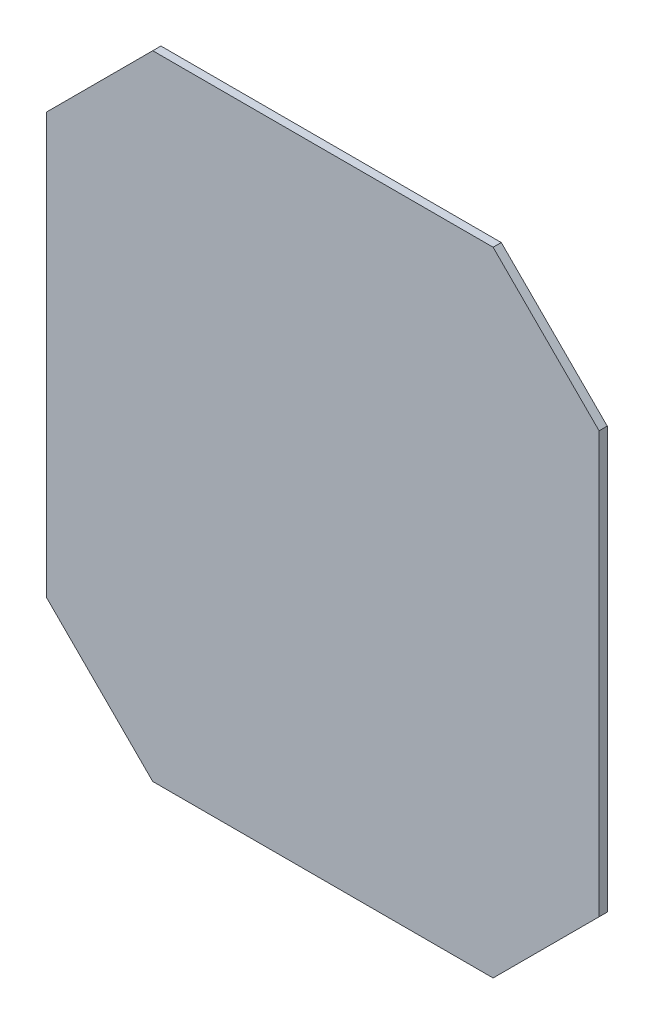
SolidWorks part; units mm, degrees
ref_plane "Front Plane" through (0, 0, 0) normal (0, 0, 1) x (1, 0, 0)
ref_plane "Top Plane" through (0, 0, 0) normal (0, 1, 0) x (1, 0, 0)
ref_plane "Right Plane" through (0, 0, 0) normal (1, 0, 0) x (0, 0, -1)
sketch "Sketch1" plane through (0, 0, 0) normal (0, 0, 1) x (1, 0, 0)
  line L1 (-150.1314, -197.3914) -> (150.1314, -197.3914)
  line L2 (-150.1314, -197.3914) -> (-150.1314, -537.1114)
  line L3 (-150.1314, -537.1114) -> (150.1314, -537.1114)
  line L4 (150.1314, -197.3914) -> (150.1314, -537.1114)
  line L5 (-150.1314, -197.3914) -> (150.1314, -537.1114) construction
  line L6 (-150.1314, -537.1114) -> (150.1314, -197.3914) construction
  line L8 (-150.1314, -477.2514) -> (-129.8686, -477.2514) construction
  line L9 (-129.8686, -477.2514) -> (-89.8686, -517.2514) construction
  line L10 (-89.8686, -517.2514) -> (-89.8686, -537.1114) construction
  line L14 (-129.4544, -476.2514) -> (-88.8686, -516.8372)
  line L15 (-88.8686, -516.8372) -> (-88.8686, -537.1114)
  line L16 (-129.4544, -476.2514) -> (-150.1314, -476.2514)
  line L17 (0, -113.8731) -> (0, -620.6296) construction
  line L18 (88.8686, -516.8372) -> (88.8686, -537.1114)
  line L19 (89.8686, -517.2514) -> (89.8686, -537.1114) construction
  line L20 (129.8686, -477.2514) -> (89.8686, -517.2514) construction
  line L21 (129.4544, -476.2514) -> (88.8686, -516.8372)
  line L22 (129.4544, -476.2514) -> (150.1314, -476.2514)
  line L23 (150.1314, -477.2514) -> (129.8686, -477.2514) construction
  line L24 (-75.6397, -367.2514) -> (75.6397, -367.2514) construction
  line L25 (88.8686, -217.6656) -> (88.8686, -197.3914)
  line L26 (89.8686, -217.2514) -> (89.8686, -197.3914) construction
  line L27 (129.8686, -257.2514) -> (89.8686, -217.2514) construction
  line L28 (129.4544, -258.2514) -> (88.8686, -217.6656)
  line L29 (129.4544, -258.2514) -> (150.1314, -258.2514)
  line L30 (150.1314, -257.2514) -> (129.8686, -257.2514) construction
  line L31 (-89.8686, -217.2514) -> (-89.8686, -197.3914) construction
  line L32 (-88.8686, -217.6656) -> (-88.8686, -197.3914)
  line L33 (-129.8686, -257.2514) -> (-89.8686, -217.2514) construction
  line L34 (-150.1314, -257.2514) -> (-129.8686, -257.2514) construction
  line L35 (-129.4544, -258.2514) -> (-150.1314, -258.2514)
  line L36 (-129.4544, -258.2514) -> (-88.8686, -217.6656)
  point P0 (0, -367.2514)
  point P28 (0, -367.2514)
  point P39 (0, -367.2514)
extrude "Boss-Extrude1" add sketch "Sketch1" along normal blind 4 contours L36 L35 L2 L16 L14 L15 L3 L18 L21 L22 L4 L29 L28 L25 L1 L32
sketch "Sketch2" plane through (0, 0, 4) normal (0, 0, 1) x (1, 0, 0)
  line L0 (-150.1314, -258.2514) -> (-150.1314, -476.2514) construction
  line L1 (-83.3944, -212.1914) -> (83.3944, -212.1914)
  line L2 (-135.3314, -264.1283) -> (-135.3314, -470.3744)
  line L3 (-83.3944, -522.3114) -> (83.3944, -522.3114)
  line L4 (135.3314, -264.1283) -> (135.3314, -470.3744)
  line L5 (150.1314, -258.2514) -> (150.1314, -476.2514) construction
  line L6 (-88.8686, -537.1114) -> (88.8686, -537.1114) construction
  line L7 (-88.8686, -197.3914) -> (88.8686, -197.3914) construction
  line L8 (-135.3314, -264.1283) -> (-83.3944, -212.1914)
  line L9 (-189.2166, -161.3867) -> (239.9048, -161.3867)
  line L10 (-189.2166, -161.3867) -> (-189.2166, -586.1068)
  line L11 (-189.2166, -586.1068) -> (239.9048, -586.1068)
  line L12 (239.9048, -161.3867) -> (239.9048, -586.1068)
  line L13 (-129.4544, -258.2514) -> (-88.8686, -217.6656) construction
  line L14 (83.3944, -212.1914) -> (135.3314, -264.1283)
  line L15 (135.3314, -470.3744) -> (83.3944, -522.3114)
  line L16 (-135.3314, -470.3744) -> (-83.3944, -522.3114)
  line L17 (-129.4544, -476.2514) -> (-88.8686, -516.8372) construction
  line L18 (129.4544, -476.2514) -> (88.8686, -516.8372) construction
  line L19 (129.4544, -258.2514) -> (88.8686, -217.6656) construction
  dimension "D1" = 14.8
  dimension "D2" = 14.8
  dimension "D3" = 14.8
  dimension "D4" = 14.8
extrude "Cut-Extrude1" cut sketch "Sketch2" against normal blind 10
